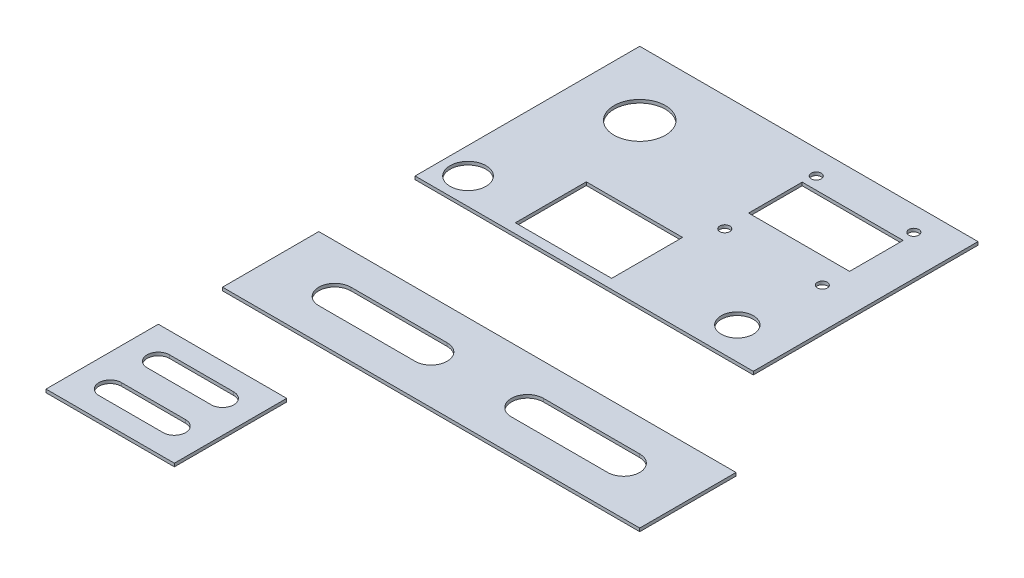
SolidWorks part; units mm, degrees
ref_plane "Front Plane" through (0, 0, 0) normal (0, 0, 1) x (1, 0, 0)
ref_plane "Top Plane" through (0, 0, 0) normal (0, 1, 0) x (1, 0, 0)
ref_plane "Right Plane" through (0, 0, 0) normal (1, 0, 0) x (0, 0, -1)
sketch "Sketch1" plane through (0, 0, 0) normal (0, 1, 0) x (1, 0, 0)
  line L0 (60, 48.25) -> (95.4, 48.25) construction
  line L1 (0, 0) -> (105.4, 0)
  line L2 (0, 0) -> (0, 70)
  line L3 (0, 70) -> (105.4, 70)
  line L4 (105.4, 0) -> (105.4, 70)
  line L5 (62.97, 57.65) -> (92.43, 57.65) construction
  line L6 (62.97, 57.65) -> (62.97, 42.95) construction
  line L7 (62.97, 42.95) -> (92.43, 42.95) construction
  line L8 (92.43, 57.65) -> (92.43, 42.95) construction
  line L9 (60, 65) -> (95.4, 65) construction
  line L10 (60, 65) -> (60, 31.5) construction
  line L11 (60, 31.5) -> (95.4, 31.5) construction
  line L12 (95.4, 65) -> (95.4, 31.5) construction
  line L13 (77.7, 65) -> (77.7, 31.5) construction
  line L14 (61.97, 58.65) -> (93.43, 58.65)
  line L15 (93.43, 58.65) -> (93.43, 41.95)
  line L16 (61.97, 41.95) -> (93.43, 41.95)
  line L17 (61.97, 58.65) -> (61.97, 41.95)
  line L19 (28.25, 25.1) -> (58.25, 25.1)
  line L20 (28.25, 25.1) -> (28.25, 3)
  line L21 (28.25, 3) -> (58.25, 3)
  line L22 (58.25, 25.1) -> (58.25, 3)
  circle A0 centre (8.25, 8.25) radius 5.59
  circle A1 centre (20, 50) radius 8
  circle A2 centre (90.4, 10) radius 5
  circle A4 centre (20, 50) radius 20 construction
  circle A5 centre (8.25, 8.25) radius 8.25 construction
  circle A6 centre (62.5, 62.5) radius 1.55
  circle A10 centre (92.9, 62.5) radius 1.55
  circle A11 centre (92.9, 34) radius 1.55
  circle A12 centre (62.5, 34) radius 1.55
  point P35 (77.7, 57.65)
  dimension "D1" = 11.18
  dimension "D2" = 16
  dimension "D3" = 40
  dimension "D4" = 16.5
  dimension "D5" = 10
  dimension "D6" = 3.1
  dimension "D16" = 40
  dimension "D23" = 20
  dimension "D7" = 2.5
  dimension "D8" = 2.5
  dimension "D9" = 35.4
  dimension "D10" = 33.5
  dimension "D11" = 14.7
  dimension "D12" = 29.46
  dimension "D13" = 7.35
  dimension "D15" = 5
  dimension "D17" = 50
  dimension "D18" = 10
  dimension "D19" = 10
  dimension "D20" = 22.1
  dimension "D21" = 30
  dimension "D22" = 15
  dimension "D24" = 3
  dimension "D14" = 1
extrude "Boss-Extrude1" add sketch "Sketch1" along normal blind 1
sketch "Sketch2" plane through (0, 0, 0) normal (0, 1, 0) x (1, 0, 0)
  line L0 (20, -45) -> (50, -45) construction
  line L1 (0, -30) -> (130, -30)
  line L2 (0, -30) -> (0, -60)
  line L3 (0, -60) -> (130, -60)
  line L4 (130, -30) -> (130, -60)
  line L5 (20, -40) -> (50, -40)
  line L6 (20, -50) -> (50, -50)
  line L7 (80, -45) -> (110, -45) construction
  line L8 (80, -40) -> (110, -40)
  line L9 (80, -50) -> (110, -50)
  line L10 (0, 70) -> (0, 0) construction
  line L11 (0, 0) -> (105.4, 0) construction
  arc A0 (20, -40) -> (20, -50) centre (20, -45) ccw
  arc A1 (50, -50) -> (50, -40) centre (50, -45) ccw
  arc A2 (80, -40) -> (80, -50) centre (80, -45) ccw
  arc A3 (110, -50) -> (110, -40) centre (110, -45) ccw
  point P6 (35, -45)
  point P13 (95, -45)
  dimension "D2" = 5
  dimension "D1" = 30
  dimension "D3" = 30
  dimension "D4" = 10
  dimension "D5" = 10
  dimension "D6" = 20
  dimension "D7" = 20
  dimension "D8" = 30
extrude "Boss-Extrude2" add sketch "Sketch2" along normal blind 1 separate body
sketch "Sketch3" plane through (0, 0, 0) normal (0, 1, 0) x (1, 0, 0)
  line L0 (10, -90) -> (30, -90) construction
  line L1 (0, -80) -> (40, -80)
  line L2 (0, -80) -> (0, -115)
  line L3 (0, -115) -> (40, -115)
  line L4 (40, -80) -> (40, -115)
  line L5 (10, -86.5) -> (30, -86.5)
  line L6 (10, -93.5) -> (30, -93.5)
  line L7 (10, -105) -> (30, -105) construction
  line L8 (10, -101.5) -> (30, -101.5)
  line L9 (10, -108.5) -> (30, -108.5)
  line L10 (30, -90) -> (30, -105) construction
  line L11 (0, -30) -> (0, -60) construction
  line L12 (0, -60) -> (130, -60) construction
  arc A0 (10, -86.5) -> (10, -93.5) centre (10, -90) ccw
  arc A1 (30, -93.5) -> (30, -86.5) centre (30, -90) ccw
  arc A2 (10, -101.5) -> (10, -108.5) centre (10, -105) ccw
  arc A3 (30, -108.5) -> (30, -101.5) centre (30, -105) ccw
  point P6 (20, -90)
  point P13 (20, -105)
  point P20 (51.4374, -125.8042)
  dimension "D1" = 3.5
  dimension "D2" = 20
  dimension "D3" = 15
  dimension "D4" = 10
  dimension "D5" = 10
  dimension "D6" = 10
  dimension "D7" = 10
  dimension "D8" = 20
extrude "Boss-Extrude3" add sketch "Sketch3" along normal blind 1 separate body
